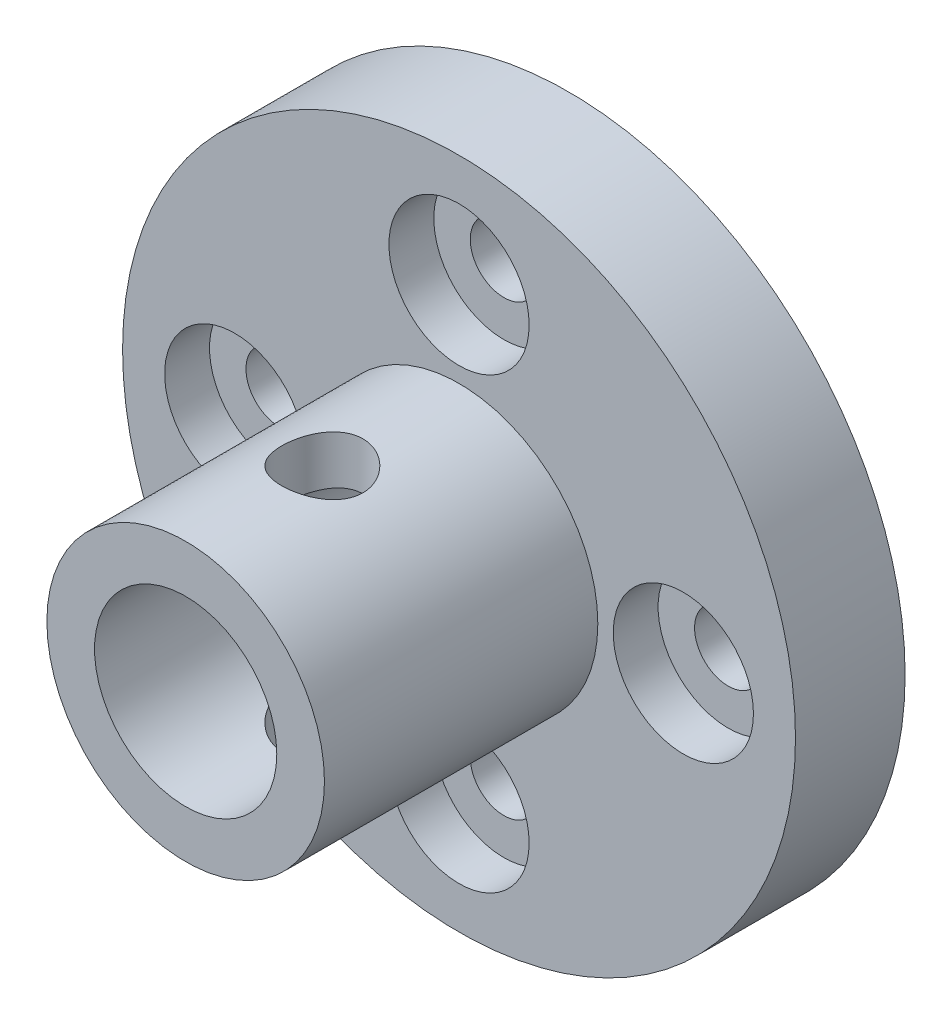
SolidWorks part; units mm, degrees
ref_plane "Plan de face" through (0, 0, 0) normal (0, 0, 1) x (1, 0, 0)
ref_plane "Plan de dessus" through (0, 0, 0) normal (0, 1, 0) x (1, 0, 0)
ref_plane "Plan de droite" through (0, 0, 0) normal (1, 0, 0) x (0, 0, -1)
sketch "Esquisse1" plane through (0, 0, 0) normal (0, 0, 1) x (1, 0, 0)
  circle A0 centre (0, 0) radius 12
  dimension "D1" = 24
extrude "Boss.-Extru.1" add sketch "Esquisse1" along normal blind 3.91
sketch "Esquisse6" plane through (0, 0, 0) normal (0, 0, -1) x (-1, 0, 0)
  circle A0 centre (0, 0) radius 4
  dimension "D1" = 8
extrude "Enlèv. mat.-Extru.2" cut sketch "Esquisse6" against normal blind 1.91
sketch "Esquisse7" plane through (0, 0, 3.91) normal (0, 0, 1) x (1, 0, 0)
  circle A1 centre (0, 0) radius 4.95
  circle A2 centre (0, 0) radius 3.25
  dimension "D1" = 6.5
  dimension "D3" = 9.9
extrude "Boss.-Extru.2" add sketch "Esquisse7" along normal blind 9.75
hole_wizard "Chambrage pour vis à tête ronde bombée M21" positions "Esquisse10" profile "Esquisse11" counterbore size "M2" standard "Ansi Metric" end condition through all
sketch "Esquisse10" plane through (0, 0, 3.91) normal (0, 0, 1) x (1, 0, 0)
  point P0 (0, 8)
  dimension "D1" = 8
sketch "Esquisse11" plane through (0, 8, 3.91) normal (1, 0, 0) x (0, -1, 0)
  line L0 (0, 0) -> (0, 3.91)
  line L1 (0, 3.91) -> (1.2, 3.91)
  line L3 (1.2, 3.91) -> (1.2, 1.6)
  line L4 (1.2, 1.6) -> (2.5, 1.6)
  line L5 (2.5, 1.6) -> (2.5, 0)
  line L7 (2.5, 0) -> (0, 0)
  line L11 (0, -6.35) -> (0, 107.95) construction
  dimension "Diamètre du perçage jusqu'au prochain" = 2.4
  dimension "Profondeur du perçage jusqu'au prochain" = 3.91
  dimension "Diamètre du chambrage" = 5
  dimension "Profondeur du chambrage" = 1.6
pattern_circular "Répétition circulaire2" count 4 every 90 about axis through (0, 0, 0) along (0, 0, 1) of "Chambrage pour vis à tête ronde bombée M21"
sketch "Esquisse12" plane through (0, 0, 0) normal (0, 1, 0) x (1, 0, 0)
  line L0 (0, -3.91) -> (0, -13.66) construction
  line L1 (-4.95, -3.91) -> (4.95, -3.91) construction
  line L2 (-4.95, -13.66) -> (4.95, -13.66) construction
  circle A0 centre (0, -8.785) radius 1.45
  point P8 (0, -8.785)
  dimension "D1" = 2.9
extrude "Enlèv. mat.-Extru.3" cut sketch "Esquisse12" against normal through all both and the other way through all
